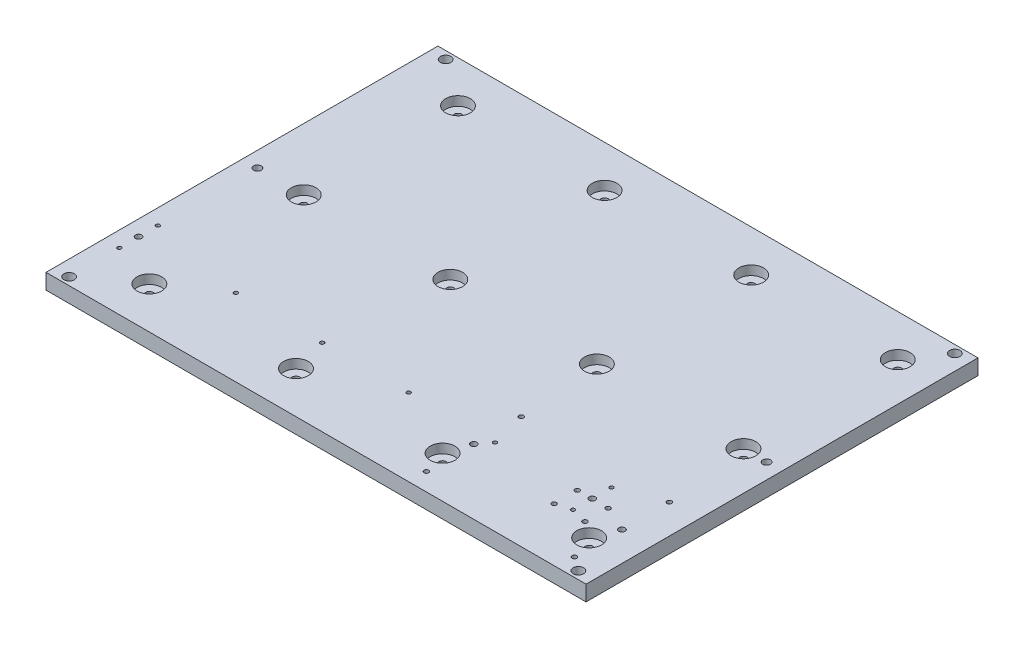
SolidWorks part; units mm, degrees
ref_plane "Front Plane" through (0, 0, 0) normal (0, 0, 1) x (1, 0, 0)
ref_plane "Top Plane" through (0, 0, 0) normal (0, 1, 0) x (1, 0, 0)
ref_plane "Right Plane" through (0, 0, 0) normal (1, 0, 0) x (0, 0, -1)
sketch "Sketch2" plane through (0, 0, 0) normal (0, 1, 0) x (1, 0, 0)
  line L5 (0, 0) -> (920, 0)
  line L6 (0, 0) -> (0, 264)
  line L7 (0, 264) -> (920, 264)
  line L8 (920, 0) -> (920, 264)
  dimension "D1" = 264
  dimension "D2" = 920
extrude "Boss-Extrude1" add sketch "Sketch2" along normal blind 10
sketch "Sketch1" plane through (0, 10, 0) normal (0, 1, 0) x (1, 0, 0)
  line L0 (0, 132) -> (920, 132) construction
  line L1 (0, 0) -> (920, 0) construction
  line L2 (0, 0) -> (0, 264) construction
  line L3 (0, 264) -> (920, 264) construction
  line L4 (920, 0) -> (920, 264) construction
  line L5 (40, 264) -> (40, 0) construction
  line L6 (0, 182) -> (920, 182) construction
  line L7 (0, 182) -> (0, 82) construction
  line L8 (0, 82) -> (920, 82) construction
  line L9 (920, 182) -> (920, 82) construction
  line L10 (0, 232) -> (920, 232) construction
  line L11 (0, 232) -> (0, 32) construction
  line L12 (0, 32) -> (920, 32) construction
  line L13 (920, 232) -> (920, 32) construction
  line L14 (0, 157) -> (920, 157) construction
  line L15 (0, 157) -> (0, 107) construction
  line L16 (0, 107) -> (920, 107) construction
  line L17 (920, 157) -> (920, 107) construction
  line L18 (0, 157) -> (920, 157) construction
  line L19 (0, 157) -> (0, 207) construction
  line L20 (0, 207) -> (920, 207) construction
  line L21 (920, 157) -> (920, 207) construction
  line L22 (920, 207) -> (0, 207) construction
  line L23 (920, 207) -> (920, 257) construction
  line L24 (920, 257) -> (0, 257) construction
  line L25 (0, 207) -> (0, 257) construction
  line L26 (0, 107) -> (920, 107) construction
  line L27 (0, 107) -> (0, 57) construction
  line L28 (0, 57) -> (920, 57) construction
  line L29 (920, 107) -> (920, 57) construction
  line L30 (920, 57) -> (0, 57) construction
  line L31 (920, 57) -> (920, 7) construction
  line L32 (920, 7) -> (0, 7) construction
  line L33 (0, 57) -> (0, 7) construction
  circle A0 centre (40, 32) radius 2.5
  circle A1 centre (135, 32) radius 2.5
  circle A2 centre (230, 32) radius 2.5
  circle A3 centre (325, 32) radius 2.5
  circle A4 centre (420, 32) radius 2.5
  circle A5 centre (515, 32) radius 2.5
  circle A6 centre (610, 32) radius 2.5
  circle A7 centre (705, 32) radius 2.5
  circle A8 centre (800, 32) radius 2.5
  circle A9 centre (895, 32) radius 2.5
  circle A10 centre (135, 132) radius 2.5
  circle A11 centre (230, 132) radius 2.5
  circle A12 centre (325, 132) radius 2.5
  circle A13 centre (420, 132) radius 2.5
  circle A14 centre (515, 132) radius 2.5
  circle A15 centre (610, 132) radius 2.5
  circle A16 centre (705, 132) radius 2.5
  circle A17 centre (800, 132) radius 2.5
  circle A18 centre (895, 132) radius 2.5
  circle A19 centre (135, 232) radius 2.5
  circle A20 centre (230, 232) radius 2.5
  circle A21 centre (325, 232) radius 2.5
  circle A22 centre (420, 232) radius 2.5
  circle A23 centre (515, 232) radius 2.5
  circle A24 centre (610, 232) radius 2.5
  circle A25 centre (705, 232) radius 2.5
  circle A26 centre (800, 232) radius 2.5
  circle A27 centre (895, 232) radius 2.5
  circle A28 centre (40, 132) radius 2.5
  circle A29 centre (40, 232) radius 2.5
  dimension "D14" = 5
  dimension "D1" = 264
  dimension "D2" = 920
  dimension "D3" = 50
  dimension "D4" = 50
  dimension "D5" = 50
  dimension "D6" = 50
  dimension "D7" = 50
  dimension "D8" = 50
  dimension "D9" = 50
  dimension "D10" = 50
  dimension "D11" = 50
  dimension "D12" = 25
  dimension "D13" = 40
  dimension "D15" = 10
  dimension "D16" = 3
extrude "Cut-Extrude2" cut sketch "Sketch1" against normal blind 18
sketch "Sketch3" plane through (0, 10, 0) normal (0, 1, 0) x (1, 0, 0)
  circle A0 centre (40, 32) radius 8
  circle A1 centre (135, 32) radius 8
  circle A2 centre (230, 32) radius 8
  circle A3 centre (325, 32) radius 8
  circle A4 centre (420, 32) radius 8
  circle A5 centre (515, 32) radius 8
  circle A6 centre (610, 32) radius 8
  circle A7 centre (705, 32) radius 8
  circle A8 centre (800, 32) radius 8
  circle A9 centre (895, 32) radius 8
  circle A10 centre (135, 132) radius 8
  circle A11 centre (230, 132) radius 8
  circle A12 centre (325, 132) radius 8
  circle A13 centre (420, 132) radius 8
  circle A14 centre (515, 132) radius 8
  circle A15 centre (610, 132) radius 8
  circle A16 centre (705, 132) radius 8
  circle A17 centre (800, 132) radius 8
  circle A18 centre (895, 132) radius 8
  circle A19 centre (135, 232) radius 8
  circle A20 centre (230, 232) radius 8
  circle A21 centre (325, 232) radius 8
  circle A22 centre (420, 232) radius 8
  circle A23 centre (515, 232) radius 8
  circle A24 centre (610, 232) radius 8
  circle A25 centre (705, 232) radius 8
  circle A26 centre (800, 232) radius 8
  circle A27 centre (895, 232) radius 8
  circle A28 centre (40, 132) radius 8
  circle A29 centre (40, 232) radius 8
  dimension "D1" = 16
  dimension "D2" = 10
  dimension "D3" = 3
extrude "Cut-Extrude3" cut sketch "Sketch3" against normal blind 6
sketch "Sketch4" plane through (0, 10, 0) normal (0, 1, 0) x (1, 0, 0)
  line L0 (0, 0) -> (920, 0) construction
  line L1 (920, 264) -> (350, 264)
  line L2 (920, 264) -> (920, 0)
  line L3 (920, 0) -> (350, 0)
  line L4 (350, 264) -> (350, 0)
  line L5 (0, 264) -> (0, 0) construction
  dimension "D1" = 350
extrude "Cut-Extrude4" cut sketch "Sketch4" against normal blind 20
sketch "Sketch5" plane through (0, 10, 0) normal (0, 1, 0) x (1, 0, 0)
  line L0 (175, 264) -> (175, 0) construction
  line L1 (175, 132) -> (350, 132) construction
  line L2 (175, 132) -> (0, 132) construction
  line L4 (0, 0) -> (350, 0)
  line L5 (350, 0) -> (350, 264)
  line L6 (350, 264) -> (0, 264)
  line L7 (0, 264) -> (0, 0)
  line L8 (0, 0) -> (350, 0)
  line L9 (350, 0) -> (350, 264)
  line L10 (350, 264) -> (0, 264)
  line L11 (0, 264) -> (0, 0)
  dimension "D3" = 350
  dimension "D4" = 264
  dimension "D1" = 0
sketch "Sketch6" plane through (0, 10, 0) normal (0, 1, 0) x (1, 0, 0)
  line L0 (40, 132) -> (0, 132) construction
  line L1 (0, 264) -> (0, 0) construction
  line L2 (20, 264) -> (20, 0) construction
  line L3 (350, 264) -> (0, 264) construction
  line L4 (0, 0) -> (350, 0) construction
  line L5 (40, 132) -> (20, 132) construction
  dimension "D1" = 20
sketch "Sketch7" plane through (0, 10, 0) normal (0, 1, 0) x (1, 0, 0)
  line L0 (350, 264) -> (0, 264) construction
  line L1 (10, 254) -> (340, 254) construction
  line L2 (10, 254) -> (10, 10) construction
  line L3 (10, 10) -> (340, 10) construction
  line L4 (340, 254) -> (340, 10) construction
  line L5 (350, 0) -> (350, 264) construction
  line L6 (175, 254) -> (175, 264) construction
  line L7 (10, 132) -> (0, 132) construction
  line L9 (175, 132) -> (0, 132) construction
  line L10 (175, 132) -> (0, 132) construction
  line L12 (20, 7.6) -> (20, 256.4) construction
  line L13 (175, 132) -> (340, 132) construction
  line L15 (175, 254) -> (175, 132) construction
  line L16 (175, 132) -> (175, 10) construction
  line L17 (175, 10) -> (175, 0) construction
  line L18 (0, 0) -> (350, 0) construction
  line L19 (340, 132) -> (350, 132) construction
  circle A1 centre (10, 254) radius 3.4
  circle A2 centre (340, 254) radius 3.4
  circle A3 centre (340, 10) radius 3.4
  circle A4 centre (10, 10) radius 3.4
  circle A6 centre (20, 132) radius 4 construction
  circle A8 centre (10, 132) radius 2.5
  circle A10 centre (340, 132) radius 2.5
  dimension "D1" = 10
  dimension "D3" = 6.8
  dimension "D5" = 5
  dimension "D6" = 8
  dimension "D7" = 6.8
  dimension "D2" = 10
  dimension "D4" = 10
extrude "Cut-Extrude5" cut sketch "Sketch7" against normal blind 20
sketch "Sketch8" plane through (0, 10, 0) normal (0, 1, 0) x (1, 0, 0)
  line L0 (350, 0) -> (350, 264) construction
  line L1 (0, 264) -> (350, 264)
  line L2 (0, 264) -> (0, 259)
  line L3 (0, 259) -> (350, 259)
  line L4 (350, 264) -> (350, 259)
  line L6 (0, 0) -> (350, 0)
  line L7 (0, 0) -> (0, 5)
  line L8 (0, 5) -> (350, 5)
  line L9 (350, 0) -> (350, 5)
  dimension "D1" = 5
extrude "Cut-Extrude6" cut sketch "Sketch8" against normal blind 10
sketch "Sketch9" plane through (0, 10, 0) normal (0, 1, 0) x (1, 0, 0)
  line L0 (10, 67.5) -> (10, 42.5) construction
  line L1 (10, 55) -> (0, 55) construction
  line L2 (0, 259) -> (0, 5) construction
  line L3 (350, 5) -> (0, 5) construction
  line L4 (157, 259) -> (157, 5) construction
  line L5 (0, 264) -> (0, 0) construction
  line L6 (0, 259) -> (350, 259) construction
  line L7 (10, 55) -> (157, 55) construction
  circle A0 centre (10, 67.5) radius 1.25
  circle A1 centre (10, 42.5) radius 1.25
  circle A2 centre (304, 67.5) radius 1.25
  circle A3 centre (304, 42.5) radius 1.25
  circle A4 centre (73, 55) radius 1.25
  circle A5 centre (129, 55) radius 1.25
  circle A6 centre (185, 55) radius 1.25
  circle A7 centre (241, 55) radius 1.25
  circle A8 centre (10, 55) radius 2
  circle A9 centre (304, 55) radius 2
  dimension "D4" = 2.5
  dimension "D5" = 157
  dimension "D6" = 56
  dimension "D7" = 28
  dimension "D8" = 4
  dimension "D1" = 50
  dimension "D2" = 10
  dimension "D3" = 25
extrude "Cut-Extrude7" cut sketch "Sketch9" against normal blind 10
sketch "Sketch10" plane through (0, 10, 0) normal (0, 1, 0) x (1, 0, 0)
  line L0 (235, 78.0136) -> (235, 47.25) construction
  line L1 (235, 47.25) -> (235, 16.4864) construction
  line L2 (235, 16.4864) -> (331, 16.4864) construction
  line L3 (331, 16.4864) -> (331, 47.25) construction
  line L4 (331, 47.25) -> (331, 78.0136) construction
  line L5 (331, 78.0136) -> (235, 78.0136) construction
  line L6 (314.5, 54.75) -> (314.5, 78.0136) construction
  line L7 (294.5, 39.75) -> (294.5, 78.0136) construction
  line L8 (294.5, 39.75) -> (331, 39.75) construction
  line L9 (314.5, 54.75) -> (331, 54.75) construction
  line L10 (350, 5) -> (0, 5) construction
  line L11 (350, 0) -> (350, 264) construction
  circle A0 centre (235, 78.0136) radius 1.5
  circle A1 centre (235, 16.4864) radius 1.5
  circle A2 centre (294.5, 39.75) radius 1.5
  circle A3 centre (314.5, 54.75) radius 1.5
  circle A4 centre (331, 16.4864) radius 1.5
  circle A5 centre (331, 47.25) radius 2
  circle A6 centre (331, 78.0136) radius 1.5
  circle A7 centre (235, 47.25) radius 2
  circle A8 centre (294.5, 54.75) radius 1.5
  circle A9 centre (314.5, 39.75) radius 1.5
  dimension "D1" = 4
  dimension "D2" = 3
  dimension "D3" = 11.4864
  dimension "D11" = 16.5
  dimension "D13" = 23.2636
  dimension "D4" = 96
  dimension "D5" = 61.5273
  dimension "D6" = 19
  dimension "D7" = 30.7636
  dimension "D8" = 30.7636
  dimension "D9" = 38.2636
  dimension "D10" = 36.5
  dimension "D12" = 23.2636
  dimension "D14" = 16.5
extrude "Cut-Extrude8" cut sketch "Sketch10" against normal blind 10
